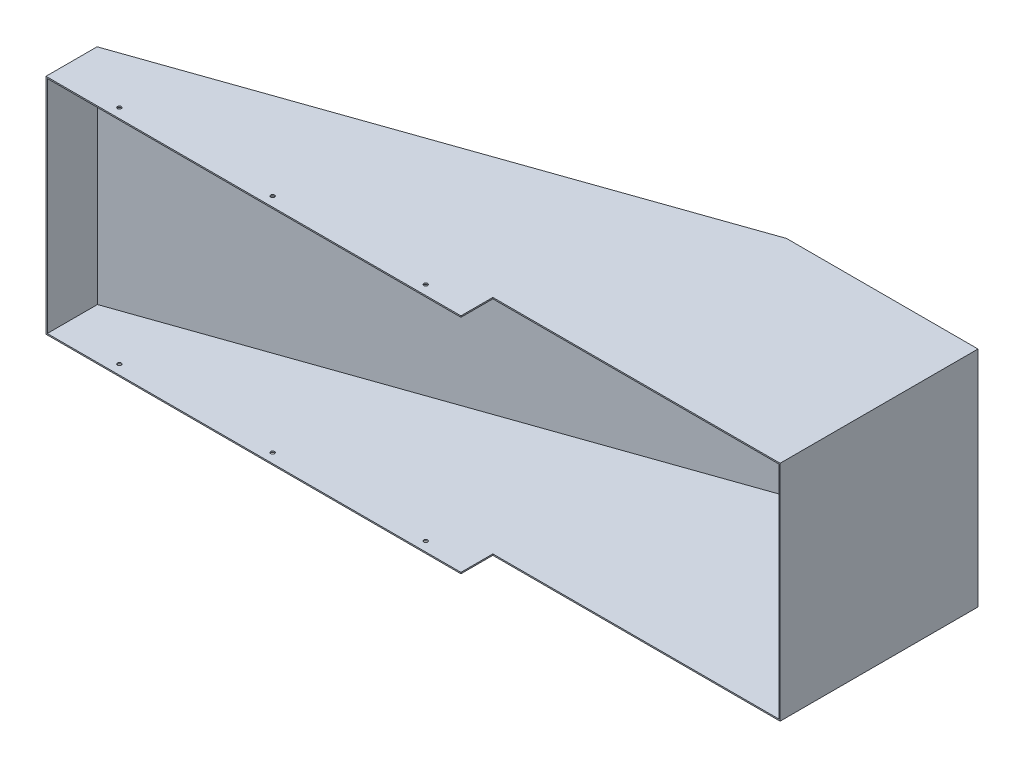
SolidWorks part; units mm, degrees
ref_plane "Front Plane" through (0, 0, 0) normal (0, 0, 1) x (1, 0, 0)
ref_plane "Top Plane" through (0, 0, 0) normal (0, 1, 0) x (1, 0, 0)
ref_plane "Right Plane" through (0, 0, 0) normal (1, 0, 0) x (0, 0, -1)
sketch "Sketch7" plane through (0, 0, 0) normal (0, 0, 1) x (1, 0, 0)
  line L1 (-400, 175) -> (400, 175)
  line L2 (-400, 175) -> (-400, -175)
  line L3 (-400, -175) -> (400, -175)
  line L4 (400, 175) -> (400, -175)
  line L5 (-400, 175) -> (400, -175) construction
  line L6 (-400, -175) -> (400, 175) construction
  point P0 (0, 0)
  dimension "D1" = 350
  dimension "D2" = 800
extrude "Boss-Extrude1" add sketch "Sketch7" along normal blind 360
sketch "Sketch8" plane through (0, -175, 0) normal (0, -1, 0) x (1, 0, 0)
  line L0 (-400, 280) -> (400, 0)
  line L1 (-400, 360) -> (-400, 0) construction
  line L2 (-400, 280) -> (-400, 0)
  line L3 (-400, 0) -> (400, 0)
  dimension "D1" = 80
extrude "Cut-Extrude1" cut sketch "Sketch8" against normal through all
sketch "Sketch10" plane through (0, -175, 0) normal (0, -1, 0) x (1, 0, 0)
  line L0 (250, 360) -> (250, 310)
  line L1 (-400, 360) -> (400, 360) construction
  line L2 (250, 310) -> (400, 310)
  line L3 (400, 360) -> (400, 0) construction
  line L4 (250, 360) -> (400, 360)
  line L5 (400, 360) -> (400, 310)
  dimension "D1" = 50
  dimension "D2" = 150
extrude "Cut-Extrude3" cut sketch "Sketch10" against normal through all
sketch "Sketch11" plane through (400, 0, 0) normal (1, 0, 0) x (0, 0, -1)
  line L4 (0, 175) -> (-310, 175)
  line L5 (-310, 175) -> (-310, -175)
  line L6 (-310, -175) -> (0, -175)
  line L7 (0, -175) -> (0, 175)
  line L8 (0, 175) -> (-310, 175)
  line L9 (-310, 175) -> (-310, -175)
  line L10 (-310, -175) -> (0, -175)
  line L11 (0, -175) -> (0, 175)
  dimension "D1" = 0
extrude "Boss-Extrude2" add sketch "Sketch11" along normal blind 300
shell "Shell3" thickness 2
sketch "Sketch12" plane through (0, -175, 0) normal (0, -1, 0) x (1, 0, 0)
  line L0 (-400, 360) -> (-400, 280) construction
  line L1 (-400, 360) -> (250, 360) construction
  circle A0 centre (-300, 345) radius 3
  circle A1 centre (-60, 345) radius 3
  circle A2 centre (180, 345) radius 3
  point P10 (0, 0)
  point P11 (0, 0)
  dimension "D1" = 6
  dimension "D2" = 100
  dimension "D3" = 240
  dimension "D4" = 240
  dimension "D5" = 15
extrude "Cut-Extrude4" cut sketch "Sketch12" against normal through all
